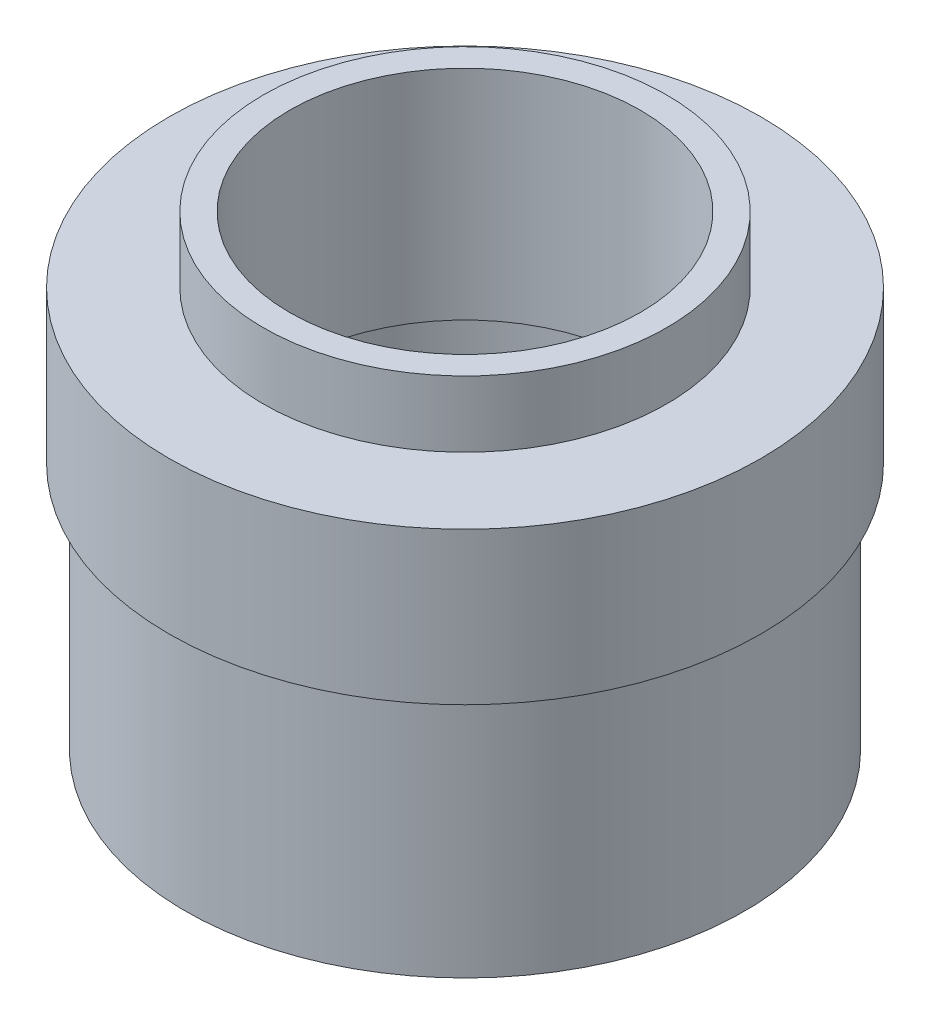
SolidWorks part; units mm, degrees
material "1060 Alloy"
ref_plane "Front Plane" through (0, 0, 0) normal (0, 0, 1) x (1, 0, 0)
ref_plane "Top Plane" through (0, 0, 0) normal (0, 1, 0) x (1, 0, 0)
ref_plane "Right Plane" through (0, 0, 0) normal (1, 0, 0) x (0, 0, -1)
sketch "Sketch1" plane through (0, 0, 0) normal (0, 0, 1) x (1, 0, 0)
  line L0 (0, 25.0698) -> (0, 0) construction
  line L1 (-18.542, 25.0698) -> (18.542, 25.0698) construction
  line L2 (-17.526, 15.5448) -> (-17.526, 0)
  line L3 (-17.526, 0) -> (17.526, 0)
  line L4 (17.526, 15.5448) -> (17.526, 0)
  line L5 (-12.6365, 25.0698) -> (-12.6365, 29.21)
  line L6 (-12.6365, 29.21) -> (12.6365, 29.21)
  line L7 (12.6365, 29.21) -> (12.6365, 25.0698)
  line L8 (18.542, 25.0698) -> (18.542, 15.5448)
  line L9 (18.542, 15.5448) -> (17.526, 15.5448)
  line L10 (0, 29.21) -> (0, 25.0698) construction
  line L11 (-18.542, 25.0698) -> (-18.542, 15.5448)
  line L12 (-18.542, 15.5448) -> (-17.526, 15.5448)
  line L13 (-18.542, 25.0698) -> (-12.6365, 25.0698)
  line L14 (12.6365, 25.0698) -> (18.542, 25.0698)
  line L15 (0, 29.21) -> (0, 0)
  point P0 (0, 0.4804)
  dimension "D1" = 35.052
  dimension "D2" = 25.0698
  dimension "D3" = 9.525
  dimension "D4" = 37.084
  dimension "D5" = 25.273
  dimension "D6" = 29.21
revolve "Revolve2" add sketch "Sketch1" angle 360 about L15
sketch "Sketch2" plane through (0, 0, 0) normal (0, -1, 0) x (1, 0, 0)
  circle A0 centre (0, 0) radius 12.319
  dimension "D1" = 24.638
extrude "Cut-Extrude2" cut sketch "Sketch2" against normal up to surface (15.5448 mm away) up to face at (-17.526, 15.5448, 0)
sketch "Sketch3" plane through (0, 29.21, 0) normal (0, 1, 0) x (1, 0, 0)
  circle A0 centre (0, 0) radius 10.9855
  dimension "D1" = 21.971
extrude "Cut-Extrude3" cut sketch "Sketch3" against normal through all
ref_plane "Plane1" through (0, 7.7724, 0) normal (0, -1, 0) x (1, 0, 0)
